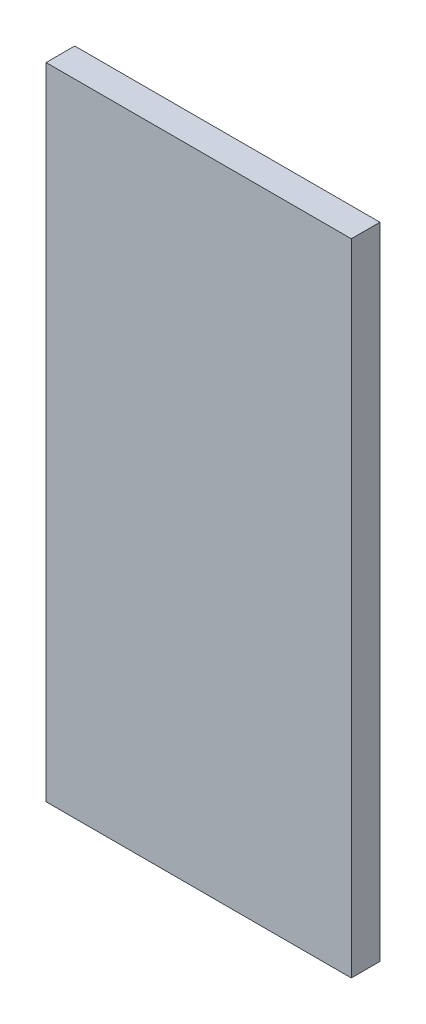
SolidWorks part; units mm, degrees
ref_plane "Front Plane" through (0, 0, 0) normal (0, 0, 1) x (1, 0, 0)
ref_plane "Top Plane" through (0, 0, 0) normal (0, 1, 0) x (1, 0, 0)
ref_plane "Right Plane" through (0, 0, 0) normal (1, 0, 0) x (0, 0, -1)
sketch "Sketch1" plane through (0, 0, 0) normal (0, 0, 1) x (1, 0, 0)
  line L1 (-47.4268, 100.0086) -> (155.7732, 100.0086)
  line L2 (-47.4268, 100.0086) -> (-47.4268, -326.2034)
  line L3 (-47.4268, -326.2034) -> (155.7732, -326.2034)
  line L4 (155.7732, 100.0086) -> (155.7732, -326.2034)
  line L5 (-47.4268, 100.0086) -> (155.7732, -326.2034) construction
  line L6 (-47.4268, -326.2034) -> (155.7732, 100.0086) construction
  point P0 (54.1732, -113.0974)
extrude "Boss-Extrude1" add sketch "Sketch1" along normal blind 19.05 contours L2 L1 L4 L3
